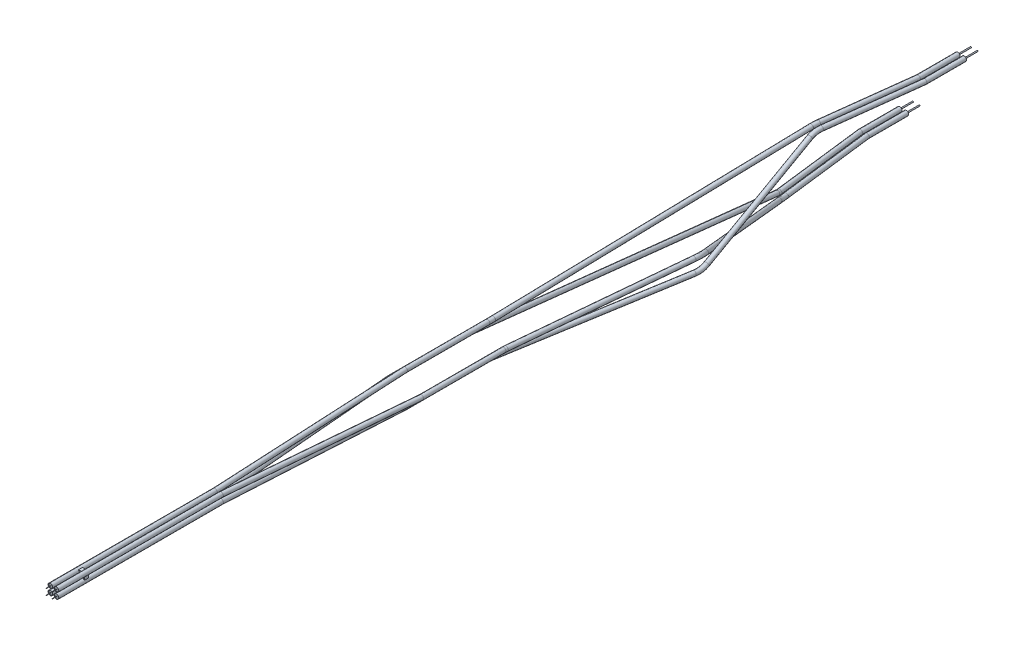
SolidWorks part; units mm, degrees
ref_plane "front P1" through (0, 0, 0) normal (0, 0, 1) x (1, 0, 0)
ref_plane "top" through (0, 0, 0) normal (0, 1, 0) x (1, 0, 0)
ref_plane "right" through (0, 0, 0) normal (1, 0, 0) x (0, 0, -1)
ref_axis "Axis1" through (0, 0, 4.3921) along (0, 0, -1)
sketch "Sketch7 Locates planes" plane through (0, 0, 0) normal (1, 0, 0) x (0, 0, -1)
  line L0 (9.5892, 0.8389) -> (16.6116, 1.4533)
  line L1 (2.54, 0) -> (9.5892, 0)
  line L2 (16.6116, 2.9291) -> (9.5892, 1.6908)
  line L3 (9.5892, 1.305) -> (16.6116, 2.2607)
  point P0 (160.655, 0)
  point P1 (84.455, 0)
  point P2 (48.3616, 0)
  point P3 (16.6116, 0)
  point P4 (135.255, 0)
  point P6 (100.33, 0)
  point P7 (0, 0)
  point P16 (186.055, 0)
  point P17 (178.435, 0)
  dimension "D2" = 31.75
  dimension "D3" = 25.4
  dimension "D4" = 101.6
  dimension "D5" = 50.8
  dimension "D6" = 15.875
  dimension "D7" = 16.6116
  dimension "D8" = 5
  dimension "D9" = 10
  dimension "D10" = 2.25
  dimension "D11" = 2.54
  dimension "D12" = 186.055
  dimension "D13" = 7.62
ref_plane "P1" through (0, 0, -186.055) normal (0, 0, 1) x (1, 0, 0)
ref_plane "Plane2" through (0, 0, -178.435) normal (0, 0, 1) x (1, 0, 0)
ref_plane "P2" through (0, 0, -160.655) normal (0, 0, 1) x (1, 0, 0)
ref_plane "P3" through (0, 0, -135.255) normal (0, 0, 1) x (1, 0, 0)
ref_plane "P4" through (0, 0, -100.33) normal (0, 0, 1) x (1, 0, 0)
ref_plane "P5" through (0, 0, -84.455) normal (0, 0, 1) x (1, 0, 0)
ref_plane "P6" through (0, 0, -48.3616) normal (0, 0, 1) x (1, 0, 0)
ref_plane "P7" through (0, 0, -16.6116) normal (0, 0, 1) x (1, 0, 0)
sketch "Sketch P1" plane through (0, 0, -186.055) normal (0, 0, 1) x (1, 0, 0)
  circle A0 centre (5.588, 7.3406) radius 0.635
  circle A1 centre (-5.588, -7.3406) radius 0.635
  point P0 (4.953, 7.3406)
  point P1 (6.223, 7.3406)
  point P3 (-6.223, -7.3406)
  point P4 (-4.953, -7.3406)
  dimension "D3" = 1.27
  dimension "D1" = 7.3406
  dimension "D2" = 5.588
  dimension "D5" = 4.953
  dimension "D4" = 5.588
  dimension "D6" = 7.3406
sketch "Sketch19" plane through (0, 0, -178.435) normal (0, 0, 1) x (1, 0, 0)
  point P0 (6.223, 7.3406)
  point P1 (4.953, 7.3406)
  point P2 (-4.953, -7.3406)
  point P3 (-6.223, -7.3406)
sketch "Sketch P2" plane through (0, 0, -160.655) normal (0, 0, 1) x (1, 0, 0)
  point P0 (2.794, 7.3406)
  point P1 (4.064, 7.3406)
  point P3 (-4.064, -7.3406)
  point P5 (-2.794, -7.3406)
  dimension "D1" = 1.27
  dimension "D2" = 2.159
  dimension "D3" = 1.27
  dimension "D4" = 2.159
sketch "Sketch P3" plane through (0, 0, -135.255) normal (0, 0, 1) x (1, 0, 0)
  point P0 (0, 2.54)
  point P1 (6.35, -2.54)
  point P2 (6.35, 0)
  point P3 (-2.54, 0)
  dimension "D1" = 6.35
  dimension "D2" = 2.54
  dimension "D3" = 2.54
  dimension "D4" = 2.54
  dimension "D5" = 6.35
sketch "Sketch P4" plane through (0, 0, -100.33) normal (0, 0, 1) x (1, 0, 0)
  point P0 (0, -3.0988)
  point P1 (0, 3.0988)
  point P2 (3.0988, 0)
  point P3 (-3.0988, 0)
sketch "Sketch P5" plane through (0, 0, -84.455) normal (0, 0, 1) x (1, 0, 0)
  point P0 (0, 3.0988)
  point P1 (0, -3.0988)
  point P3 (3.0988, 0)
  point P5 (-3.0988, 0)
sketch "Sketch P6" plane through (0, 0, -48.3616) normal (0, 0, 1) x (1, 0, 0)
  line L0 (0.7714, 0) -> (1.0924, 0) construction
  line L1 (0.0845, 0.0845) -> (0.3115, 0.3115) construction
  line L2 (-0.1415, 0.1415) -> (-0.3686, 0.3686) construction
  line L3 (-0.1088, -0.1088) -> (-0.3358, -0.3358) construction
  line L4 (0.0997, -0.0997) -> (0.3267, -0.3267) construction
  circle A0 centre (0, 0) radius 0.8262 construction
  point P0 (0.5842, 0.5842)
  point P1 (-0.5842, 0.5842)
  point P2 (-0.5842, -0.5842)
  point P3 (0.5842, -0.5842)
  dimension "D1" = 0.8262
  dimension "D2" = 45
  dimension "D3" = 0.5842
sketch "Sketch P7" plane through (0, 0, -16.6116) normal (0, 0, 1) x (1, 0, 0)
  line L0 (0.104, 0.104) -> (0.3063, 0.3063) construction
  line L1 (-0.1969, 0.1969) -> (-0.3992, 0.3992) construction
  line L2 (-0.1505, -0.1505) -> (-0.3528, -0.3528) construction
  line L3 (0.1455, -0.1455) -> (0.3478, -0.3478) construction
  line L4 (0.7362, 0) -> (1.0223, 0) construction
  circle A0 centre (0, 0) radius 0.8262 construction
  point P0 (-0.5842, 0.5842)
  point P1 (0.5842, -0.5842)
  point P4 (0.5842, 0.5842)
  point P5 (-0.5842, -0.5842)
  dimension "D1" = 0.8262
  dimension "D2" = 45
  dimension "D3" = 0.5842
sketch "Sketch3" plane through (0, 0, 0) normal (1, 0, 0) x (0, 0, -1)
  line L3 (21.6916, 0.6858) -> (22.4536, 0.6858)
  line L4 (48.3616, 0) -> (-81.8388, 0) construction
  line L5 (21.6916, 0.9398) -> (22.4536, 0.9398)
  line L6 (22.4536, 0.9398) -> (22.4536, 0.6858)
  line L10 (21.6916, 0.6858) -> (21.6916, 0.9398)
  point P1 (22.4536, 0.8128)
  dimension "D1" = 0.254
  dimension "D2" = 0.762
  dimension "D3" = 1.8796
  dimension "D4" = 1.3716
  dimension "D5" = 0.8128
  dimension "D7" = 5.08
revolve "Revolve1" add sketch "Sketch3" angle 360 about L4
sketch3d "3DSketch1"
  line L0 (4.953, 7.3406, -186.055) -> (4.953, 7.3406, -178.435)
  line L1 (2.7637, 7.2946, -160.0063) -> (0.0251, 3.1369, -101.4051)
  line L2 (0, 3.0988, -84.455) -> (-0.5842, 0.5842, -48.3616)
  line L4 (0, 3.0988, -100.33) -> (0, 3.0988, -84.455)
  line L5 (-0.5842, 0.5842, -48.3616) -> (-0.5842, 0.5842, -16.6116)
  line L6 (4.953, 7.3406, -178.435) -> (2.8725, 7.3406, -161.3013)
  arc A0 (2.7637, 7.2946, -160.0063) -> (2.8725, 7.3406, -161.3013) centre (11.9817, -1.4394, -160.1952) ccw
  arc A1 (0.0251, 3.1369, -101.4051) -> (0, 3.0988, -100.33) centre (6.986, 13.7048, -100.33) ccw
  point P8 (2.794, 7.3406, -160.655)
  point P11 (3.2658, -10.6155, -161.2535)
  point P19 (-3.62, 20.6907, -100.33)
  dimension "D1" = 12.7
  dimension "D2" = 12.7
sketch "Sketch4" plane through (0, 0, -186.055) normal (0, 0, 1) x (1, 0, 0)
  circle A0 centre (4.953, 7.3406) radius 0.4483
  dimension "D1" = 0.8966
sketch "Sketch21" plane through (0, 0, 0) normal (1, 0, 0) x (0, 0, -1)
  line L0 (15.8496, 0) -> (17.8816, 0)
  line L1 (17.8816, 0) -> (17.8816, 0.1905)
  line L2 (17.8816, 0.1905) -> (17.1196, 0.1905)
  line L3 (17.1196, 0.1905) -> (17.0561, 0.127)
  line L4 (17.0561, 0.127) -> (15.8496, 0.127)
  line L5 (15.8496, 0.127) -> (15.8496, 0)
  line L6 (19.9638, 0) -> (21.2415, 0) construction
  dimension "D1" = 0.254
  dimension "D2" = 0.381
  dimension "D3" = 0.762
  dimension "D4" = 2.032
  dimension "D5" = 0.762
  dimension "D6" = 45
revolve "Revolve3" [suppressed] add sketch "Sketch21" angle 360 about L6
sweep "SW-00 Coax Jacket X Upper" add profiles "Sketch4" path "3DSketch1"
sketch "Sketch8" plane through (0, 0, -186.055) normal (0, 0, 1) x (1, 0, 0)
  circle A0 centre (6.223, 7.3406) radius 0.4483
  dimension "D1" = 0.8966
sketch3d "3DSketch2"
  line L0 (6.223, 7.3406, -186.055) -> (6.223, 7.3406, -178.435)
  line L1 (4.0316, 6.9133, -158.4758) -> (6.2405, -2.0937, -136.3513)
  line L2 (6.1346, -2.559, -134.0861) -> (0.0844, -3.0914, -101.2541)
  line L3 (0, -3.0988, -100.33) -> (0, -3.0988, -84.455)
  line L4 (0, -3.0988, -84.455) -> (0.5842, -0.5842, -48.3616)
  line L5 (0.5842, -0.5842, -48.3616) -> (0.5842, -0.5842, -16.6116)
  line L6 (6.223, 7.3406, -178.435) -> (4.064, 7.3406, -160.655)
  arc A0 (6.2405, -2.0937, -136.3513) -> (6.1346, -2.559, -134.0861) centre (3.2212, 1.576, -134.5559) ccw
  arc A1 (4.064, 7.3406, -160.655) -> (4.0316, 6.9133, -158.4758) centre (6.4586, 2.8698, -160.3642) ccw
  arc A2 (0, -3.0988, -100.33) -> (0.0844, -3.0914, -101.2541) centre (5.0604, -2.6535, -100.33) ccw
  point P7 (6.35, -2.54, -135.255)
  point P12 (-0.8373, -1.3739, -135.3516)
  point P17 (10.8968, 5.2821, -159.8253)
  point P20 (5.5058, -7.7139, -100.33)
  dimension "D1" = 5.08
  dimension "D2" = 5.08
  dimension "D3" = 5.08
sweep "SW-00 Coax Jacket X Lower" add profiles "Sketch8" path "3DSketch2"
sketch "Sketch9" plane through (0, 0, -186.055) normal (0, 0, 1) x (1, 0, 0)
  circle A0 centre (-6.223, -7.3406) radius 0.4483
  dimension "D1" = 0.8966
sketch3d "3DSketch3"
  line L0 (-6.223, -7.3406, -186.055) -> (-6.223, -7.3406, -178.435)
  line L1 (-4.0362, -7.3158, -160.2494) -> (-3.0988, 0, -100.33)
  line L3 (-3.0988, 0, -100.33) -> (-3.0988, 0, -84.455)
  line L4 (-3.0988, 0, -84.455) -> (-0.5842, -0.5842, -48.3616)
  line L5 (-0.5842, -0.5842, -48.3616) -> (-0.5842, -0.5842, -16.6116)
  line L6 (-6.223, -7.3406, -178.435) -> (-4.064, -7.3406, -160.655)
  arc A0 (-4.064, -7.3406, -160.655) -> (-4.0362, -7.3158, -160.2494) centre (-5.7082, -5.4149, -160.4553) ccw
  point P13 (-7.6199, -7.0712, -160.2232)
  point P14 (-3.0988, 0, -100.33)
  dimension "D2" = 2.54
sweep "Sweep3" add profiles "Sketch9" path "3DSketch3"
sketch "Sketch10" plane through (0, 0, -186.055) normal (0, 0, 1) x (1, 0, 0)
  circle A0 centre (-4.953, -7.3406) radius 0.4483
  dimension "D1" = 0.8966
sketch3d "3DSketch4"
  line L0 (-4.953, -7.3406, -186.055) -> (-4.953, -7.3406, -178.435)
  line L1 (-2.3775, -7.092, -158.9144) -> (5.9003, -0.3654, -136.474)
  line L2 (6.2241, 0, -133.9112) -> (3.121, 0, -100.8041)
  line L3 (3.0988, 0, -100.33) -> (3.0988, 0, -84.455)
  line L4 (3.0988, 0, -84.455) -> (0.5842, 0.5842, -48.3616)
  line L5 (0.5842, 0.5842, -48.3616) -> (0.5842, 0.5842, -16.6116)
  line L6 (-4.953, -7.3406, -178.435) -> (-2.794, -7.3406, -160.655)
  arc A0 (3.121, 0, -100.8041) -> (3.0988, 0, -100.33) centre (8.1788, 0, -100.33) ccw
  arc A1 (5.9003, -0.3654, -136.474) -> (6.2241, 0, -133.9112) centre (1.9849, -2.771, -134.3086) ccw
  arc A2 (-2.794, -7.3406, -160.655) -> (-2.3775, -7.092, -158.9144) centre (0.4024, -3.4114, -161.0431) ccw
  point P15 (8.1788, 5.08, -100.33)
  point P18 (6.35, 0, -135.255)
  point P19 (4.7438, -7.0287, -134.05)
  point P27 (-3.4981, -0.1915, -160.5695)
  dimension "D1" = 5.08
  dimension "D2" = 5.08
sweep "Sweep4" add profiles "Sketch10" path "3DSketch4"
sketch "Sketch16" plane through (0, 0, 0) normal (1, 0, 0) x (0, 0, -1)
  line L0 (46.3296, 0) -> (48.3616, 0) construction
  line L1 (48.3616, 1.27) -> (50.3936, 1.27)
  line L2 (48.3616, 1.27) -> (48.3616, 1.016)
  line L3 (48.3616, 1.016) -> (50.3936, 1.016)
  line L4 (50.3936, 1.27) -> (50.3936, 1.016)
  dimension "D1" = 0.254
  dimension "D2" = 2.032
  dimension "D3" = 2.54
  dimension "D4" = 31.75
revolve "Revolve2" [suppressed] add sketch "Sketch16" angle 360 about L0
sketch "Sketch5" plane through (0, 0, -186.055) normal (0, 0, 1) x (1, 0, 0)
  circle A0 centre (4.953, 7.3406) radius 0.1016
  circle A1 centre (6.223, 7.3406) radius 0.1016
  circle A2 centre (-4.953, -7.3406) radius 0.1016
  circle A3 centre (-6.223, -7.3406) radius 0.1016
  dimension "D1" = 0.2032
extrude "Pin LNA End" add sketch "Sketch5" against normal blind 2.54
sketch "Sketch6" plane through (0, 0, -16.6116) normal (0, 0, 1) x (1, 0, 0)
  circle A0 centre (-0.5842, 0.5842) radius 0.1016
  dimension "D1" = 0.2032
extrude "Pin Tip End" [suppressed] add sketch "Sketch6" along normal blind 7.62
mirror "Mirror1" [suppressed] about plane through (0, 0, 0) normal (0, 1, 0)
mirror "Mirror2" [suppressed] about plane through (0, 0, 0) normal (1, 0, 0)
ref_plane "Plane3" through (0, 0, 0) normal (0.7071, 0.7071, 0) x (0, 0, -1)
sketch "Sketch15" plane through (0, 0, -16.6116) normal (0, 0, 1) x (1, 0, 0)
  circle A2 centre (-0.5842, 0.5842) radius 0.3429
  dimension "D1" = 0.6858
extrude "Extrude1" cut sketch "Sketch15" against normal blind 0.0508
sketch "Sketch12" plane through (0, 0, -16.6624) normal (0, 0, 1) x (1, 0, 0)
  circle A0 centre (-0.5842, 0.5842) radius 0.0356
  dimension "D1" = 0.0711
sketch "Sketch11" plane through (0, 0, 0) normal (0.7071, 0.7071, 0) x (0, 0, -1)
  line L0 (16.6116, 0.8262) -> (15.7988, 0.8262)
  line L1 (15.54, 1.292) -> (16.1036, 2.1978) construction
  line L2 (16.5345, 3.2392) -> (16.1637, 2.3162) construction
  line L3 (16.6116, 0.8262) -> (17.2292, 0.8262)
  arc A0 (15.7988, 0.8262) -> (15.54, 1.292) centre (15.7988, 1.131) cw construction
  arc A1 (16.1036, 2.1978) -> (16.1637, 2.3162) centre (15.4566, 2.6003) ccw construction
  dimension "D1" = 0.3048
  dimension "D5" = 0.762
  dimension "D2" = 10
  dimension "D3" = 0.8128
  dimension "D4" = 2.413
  dimension "D6" = 1.3716
pattern_circular "CirPattern3" count 4 over 360 about axis through (0, 0, 0) along (0, 0, 1) of "Extrude1"
sketch "Sketch14" plane through (0, 0, -16.6116) normal (0, 0, 1) x (1, 0, 0)
  line L1 (-1.5, 1.5) -> (1.5, 1.5)
  line L2 (-1.5, 1.5) -> (-1.5, -1.5)
  line L3 (-1.5, -1.5) -> (1.5, -1.5)
  line L4 (1.5, 1.5) -> (1.5, -1.5)
  circle A0 centre (0, 0) radius 1.3462
  point P4 (1.5, 0)
  point P5 (0, 1.5)
  dimension "D2" = 2.6924
  dimension "D1" = 3
sweep "Sweep5" add profiles "Sketch12" path "Sketch11"
pattern_circular "CirPattern1" count 4 over 360 about axis through (0, 0, 4.3921) along (0, 0, -1) of "Sweep5"
sketch "Sketch17" plane through (0, 0, 0) normal (1, 0, 0) x (0, 0, -1)
  line L1 (16.129, 2.0828) -> (17.653, 2.0828)
  line L2 (16.129, 2.0828) -> (16.129, 1.5748)
  line L3 (16.129, 1.5748) -> (17.653, 1.5748)
  line L4 (17.653, 2.0828) -> (17.653, 1.5748)
  dimension "D1" = 1.5748
  dimension "D2" = 1.524
  dimension "D3" = 0.508
  dimension "D4" = 0.0254
extrude "Boss-Extrude1" [suppressed] add sketch "Sketch17" along normal mid plane 0.762
pattern_circular "CirPattern2" [suppressed] count 4 over 360 about axis through (0, 0, 4.3921) along (0, 0, -1)
sketch "Sketch20" plane through (0, 0, -21.6916) normal (0, 0, 1) x (1, 0, 0)
  line L0 (-0.4287, 0.5353) -> (-0.5877, 0.7333)
  line L1 (-0.5901, 0.3495) -> (-0.828, 0.4447)
  arc A0 (-0.4287, 0.5353) -> (-0.5901, 0.3495) centre (0, 0) ccw
  arc A1 (-0.5877, 0.7333) -> (-0.828, 0.4447) centre (0, 0) ccw
  circle A2 centre (0, 0) radius 0.6858 construction
  circle A3 centre (0, 0) radius 0.9398 construction
extrude "Boss-Extrude2" [suppressed] add sketch "Sketch20" along normal blind 1.524
